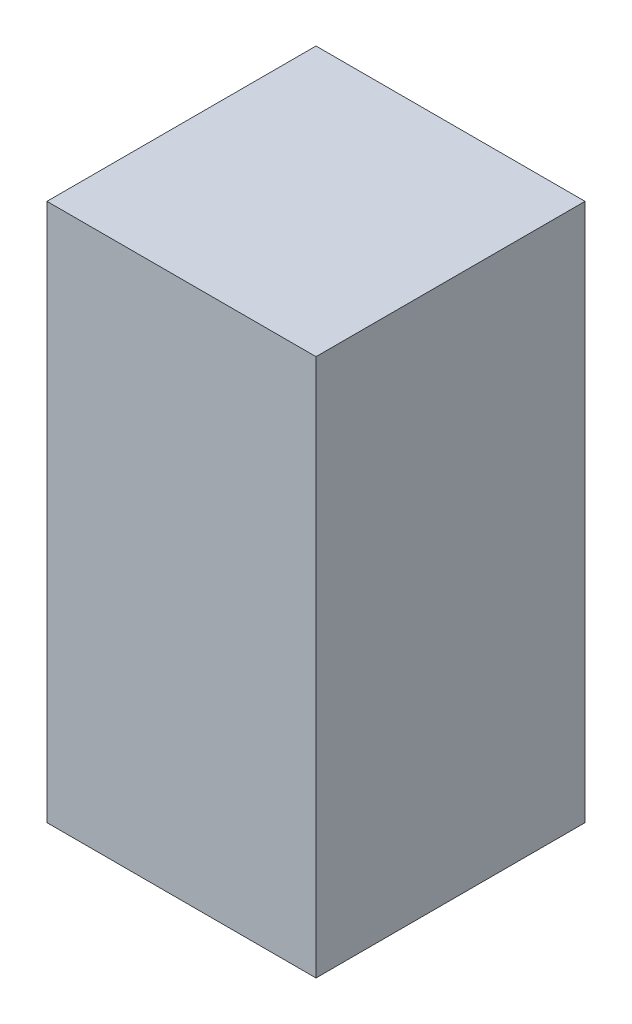
SolidWorks part; units mm, degrees
ref_plane "Front Plane" through (0, 0, 0) normal (0, 0, 1) x (1, 0, 0)
ref_plane "Top Plane" through (0, 0, 0) normal (0, 1, 0) x (1, 0, 0)
ref_plane "Right Plane" through (0, 0, 0) normal (1, 0, 0) x (0, 0, -1)
other "Configuration Table"
sketch "Sketch1" plane through (0, 0, 0) normal (0, 0, 1) x (1, 0, 0)
  line L1 (135, 470) -> (165, 470)
  line L2 (135, 470) -> (135, 530)
  line L3 (135, 530) -> (165, 530)
  line L4 (165, 470) -> (165, 530)
extrude "PACK_lineer_rulman_1_1" add sketch "Sketch1" against normal blind 30 from offset 385 separate body
